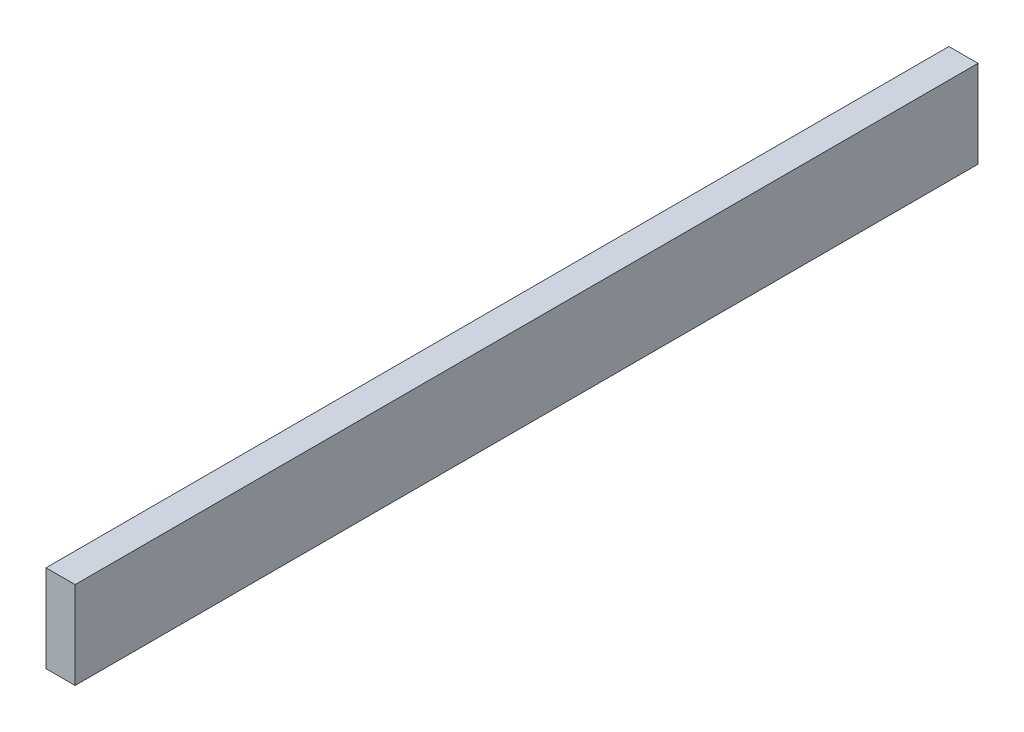
SolidWorks part; units mm, degrees
ref_plane "Front Plane" through (0, 0, 0) normal (0, 0, 1) x (1, 0, 0)
ref_plane "Top Plane" through (0, 0, 0) normal (0, 1, 0) x (1, 0, 0)
ref_plane "Right Plane" through (0, 0, 0) normal (1, 0, 0) x (0, 0, -1)
sketch "Sketch1" plane through (0, 0, 0) normal (1, 0, 0) x (0, 0, -1)
  line L1 (0, 0) -> (393.7, 0)
  line L2 (0, 0) -> (0, 38.1)
  line L3 (0, 38.1) -> (393.7, 38.1)
  line L4 (393.7, 0) -> (393.7, 38.1)
  dimension "D1" = 393.7
  dimension "D2" = 38.1
extrude "Boss-Extrude1" add sketch "Sketch1" along normal blind 12.7
